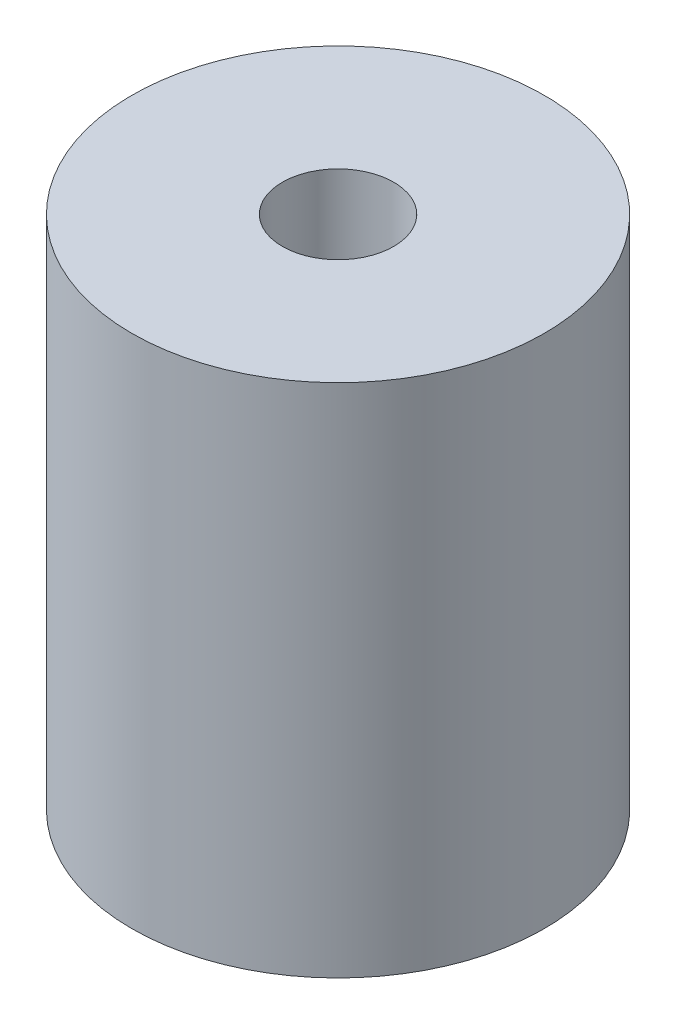
SolidWorks part; units mm, degrees
ref_plane "Front Plane" through (0, 0, 0) normal (0, 0, 1) x (1, 0, 0)
ref_plane "Top Plane" through (0, 0, 0) normal (0, 1, 0) x (1, 0, 0)
ref_plane "Right Plane" through (0, 0, 0) normal (1, 0, 0) x (0, 0, -1)
sketch "Sketch1" plane through (0, 0, 0) normal (0, 1, 0) x (1, 0, 0)
  circle A0 centre (0, 0) radius 10
  dimension "D1" = 20
extrude "Boss-Extrude1" add sketch "Sketch1" along normal mid plane 25
sketch "Sketch2" plane through (0, 0, 0) normal (0, 1, 0) x (1, 0, 0)
  circle A0 centre (0, 0) radius 2.7
  dimension "D1" = 5.4
extrude "Cut-Extrude1" cut sketch "Sketch2" along normal up to surface (12.5 mm away) up to face at (0, 12.5, 10)
sketch "Sketch3" plane through (0, 0, 0) normal (0, 1, 0) x (1, 0, 0)
  circle A0 centre (0, 0) radius 4.2
  dimension "D1" = 8.4
extrude "Cut-Extrude2" cut sketch "Sketch3" against normal up to surface (12.5 mm away) up to face at (0, -12.5, 10)
